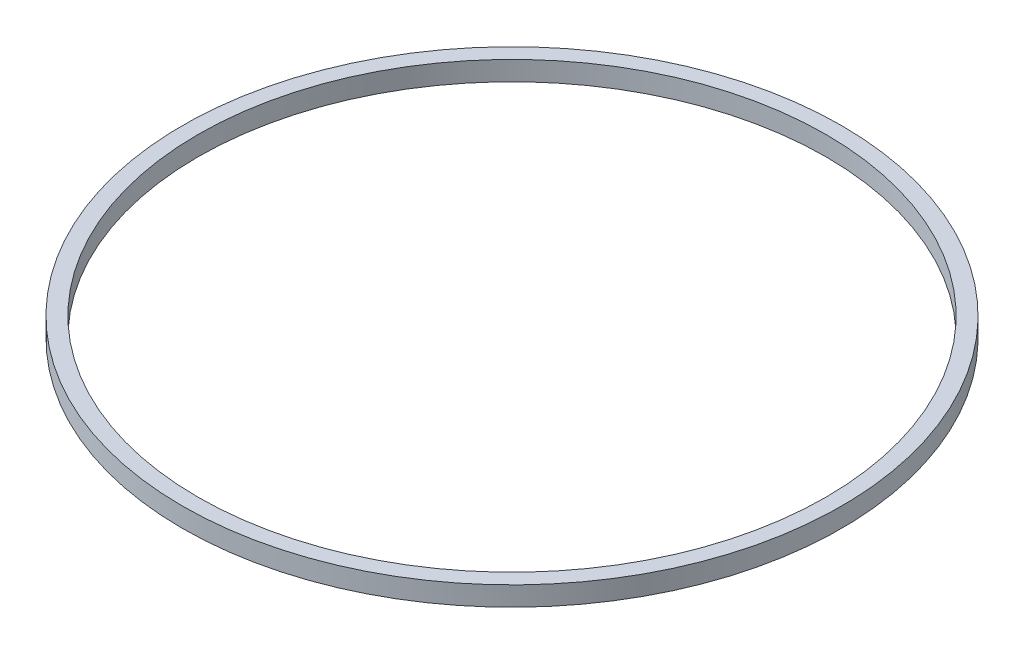
SolidWorks part; units mm, degrees
ref_plane "Front Plane" through (0, 0, 0) normal (0, 0, 1) x (1, 0, 0)
ref_plane "Top Plane" through (0, 0, 0) normal (0, 1, 0) x (1, 0, 0)
ref_plane "Right Plane" through (0, 0, 0) normal (1, 0, 0) x (0, 0, -1)
sketch "Sketch1" plane through (0, 0, 0) normal (0, 1, 0) x (1, 0, 0)
  circle A0 centre (0, 0) radius 85
  circle A1 centre (0, 0) radius 81
  dimension "D2" = 170
  dimension "D1" = 162
extrude "Boss-Extrude1" add sketch "Sketch1" along normal blind 5
equation "\"ufo_diameter\"= 170mm"
equation "\"D2@Sketch1\"=\"ufo_diameter\""
equation "\"ufo_radius\"= \"ufo_diameter\" / 2"
equation "\"ufo_inner_radius\"= \"ufo_diameter\" - 8"
equation "\"D1@Sketch1\"=\"ufo_inner_radius\""
